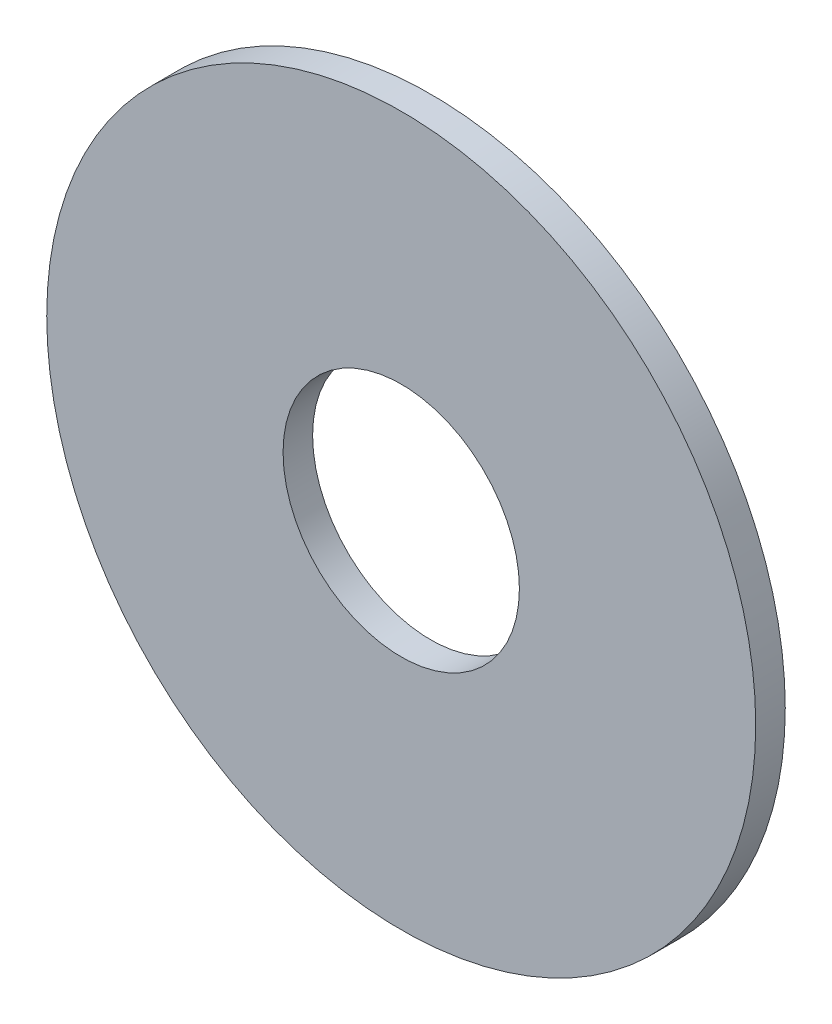
SolidWorks part; units mm, degrees
material "1.0503 (C45)"
ref_plane "前视基准面" through (0, 0, 0) normal (0, 0, 1) x (1, 0, 0)
ref_plane "上视基准面" through (0, 0, 0) normal (0, 1, 0) x (1, 0, 0)
ref_plane "右视基准面" through (0, 0, 0) normal (1, 0, 0) x (0, 0, -1)
other "Configuration Table"
sketch "草图1" plane through (0, 0, 0) normal (0, 0, 1) x (1, 0, 0)
  line L0 (-9.098, 0) -> (2.1323, 0) construction
  line L1 (0, 3.9004) -> (0, -3.1541) construction
  circle A0 centre (0, 0) radius 2
  circle A1 centre (0, 0) radius 6
  dimension "D1" = 4
  dimension "D2" = 12
extrude "凸台-拉伸1" add sketch "草图1" along normal blind 0.5
